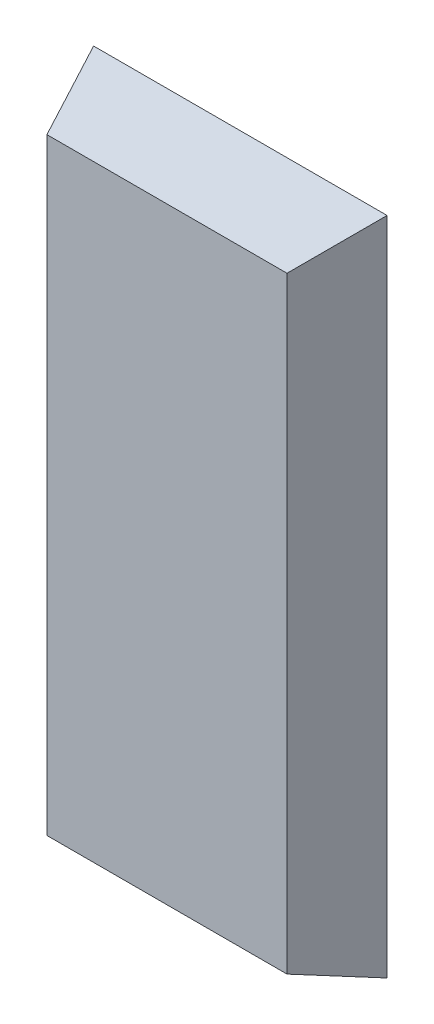
SolidWorks part; units mm, degrees
ref_plane "Front Plane" through (0, 0, 0) normal (0, 0, 1) x (1, 0, 0)
ref_plane "Top Plane" through (0, 0, 0) normal (0, 1, 0) x (1, 0, 0)
ref_plane "Right Plane" through (0, 0, 0) normal (1, 0, 0) x (0, 0, -1)
sketch "Sketch1" plane through (0, 0, 0) normal (0, 0, 1) x (1, 0, 0)
  line L1 (-10, 22.5) -> (10, 22.5)
  line L2 (-10, 22.5) -> (-10, -22.5)
  line L3 (-10, -22.5) -> (10, -22.5)
  line L4 (10, 22.5) -> (10, -22.5)
  line L5 (-10, 22.5) -> (10, -22.5) construction
  line L6 (-10, -22.5) -> (10, 22.5) construction
  point P0 (0, 0)
  dimension "D1" = 45
  dimension "D2" = 20
extrude "Boss-Extrude1" add sketch "Sketch1" along normal blind 5 draft 20
